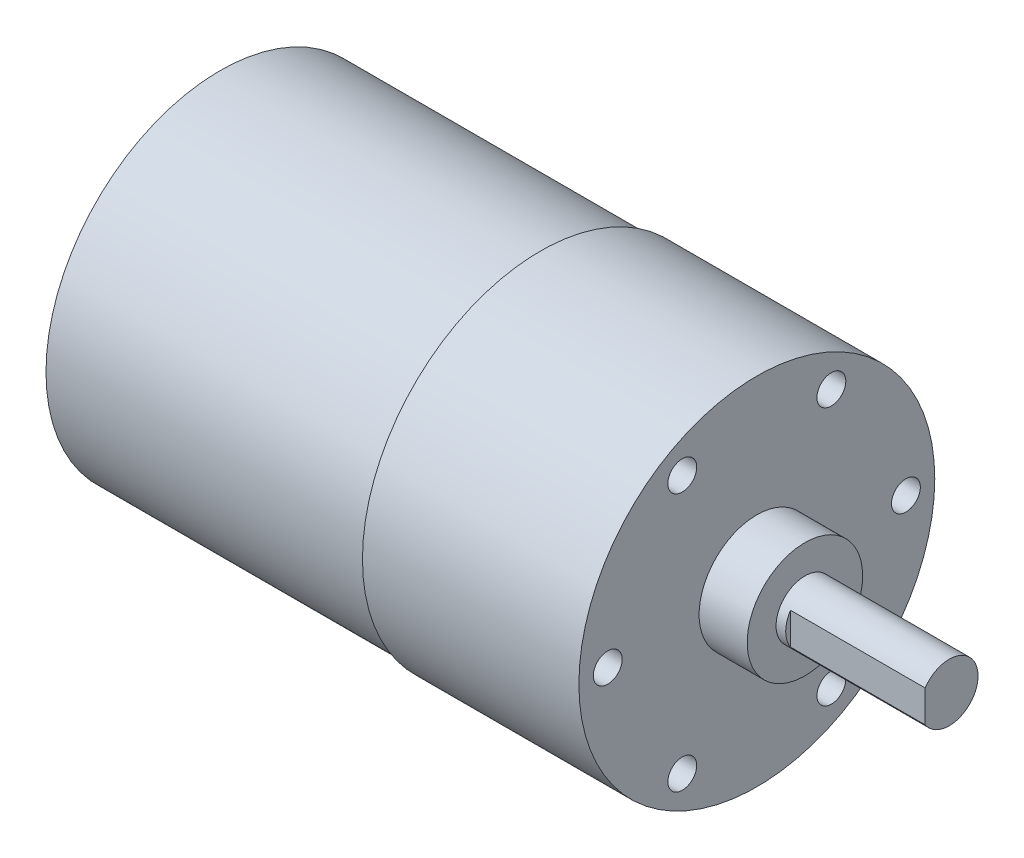
SolidWorks part; units mm, degrees
ref_plane "Front Plane" through (0, 0, 0) normal (1, 0, 0) x (0, 1, 0)
ref_plane "Top Plane" through (0, 0, 0) normal (0, 0, 1) x (0, 1, 0)
ref_plane "Right Plane" through (0, 0, 0) normal (0, 1, 0) x (-1, 0, 0)
sketch "Sketch1" plane through (0, 0, 0) normal (1, 0, 0) x (0, 1, 0)
  circle A0 centre (0, 0) radius 18.5
  dimension "D1" = 37
extrude "Boss-Extrude1" add sketch "Sketch1" along normal blind 22.5
sketch "Sketch2" plane through (22.5, 0, 0) normal (1, 0, 0) x (0, 1, 0)
  circle A0 centre (0, 0) radius 6
  dimension "D1" = 12
extrude "Boss-Extrude2" add sketch "Sketch2" along normal blind 5
sketch "Sketch3" plane through (27.5, 0, 0) normal (1, 0, 0) x (0, 1, 0)
  circle A0 centre (0, 0) radius 3
extrude "Boss-Extrude3" add sketch "Sketch3" along normal blind 15
sketch "Sketch4" plane through (42.5, 0, 0) normal (1, 0, 0) x (0, 1, 0)
  line L0 (-1.6583, 2.5) -> (1.6583, 2.5)
  circle A0 centre (0, 0) radius 3 construction
  dimension "D2" = 6
  dimension "D1" = 2.5
extrude "Cut-Extrude1" cut sketch "Sketch4" against normal blind 14 and the other way through all
sketch "Sketch5" plane through (0, 0, 0) normal (-1, 0, 0) x (0, -1, 0)
  circle A0 centre (0, 0) radius 18.1
  dimension "D1" = 36.2
extrude "Boss-Extrude4" add sketch "Sketch5" along normal blind 33.3
sketch "Sketch6" plane through (-33.3, 0, 0) normal (-1, 0, 0) x (0, -1, 0)
  line L1 (-6.6729, -4.1781) -> (-4.9295, -4.1781)
  line L2 (-6.6729, -4.1781) -> (-6.6729, 5.2)
  line L3 (-6.6729, 5.2) -> (-4.9295, 5.2)
  line L4 (-4.9295, -4.1781) -> (-4.9295, 5.2)
  line L5 (5.1099, -4.1781) -> (6.9735, -4.1781)
  line L6 (5.1099, -4.1781) -> (5.1099, 5.2)
  line L7 (5.1099, 5.2) -> (6.9735, 5.2)
  line L8 (6.9735, -4.1781) -> (6.9735, 5.2)
extrude "Boss-Extrude5" add sketch "Sketch6" along normal blind 4
sketch "Sketch7" plane through (22.5, 0, 0) normal (1, 0, 0) x (0, 1, 0)
  circle A0 centre (0, 0) radius 15.5
  circle A1 centre (0, 15.5) radius 1.5
  circle A2 centre (13.4234, 7.75) radius 1.5
  circle A3 centre (13.4234, -7.75) radius 1.5
  circle A4 centre (0, -15.5) radius 1.5
  circle A5 centre (-13.4234, -7.75) radius 1.5
  circle A6 centre (-13.4234, 7.75) radius 1.5
  point P3 (0, 15.5)
  point P4 (0, -15.5)
  point P20 (0, 0)
  dimension "D1" = 31
  dimension "D2" = 3
  dimension "D3" = 6
extrude "Cut-Extrude2" cut sketch "Sketch7" against normal blind 5 contours A4 | A5 | A6 | A1 | A2 | A3
